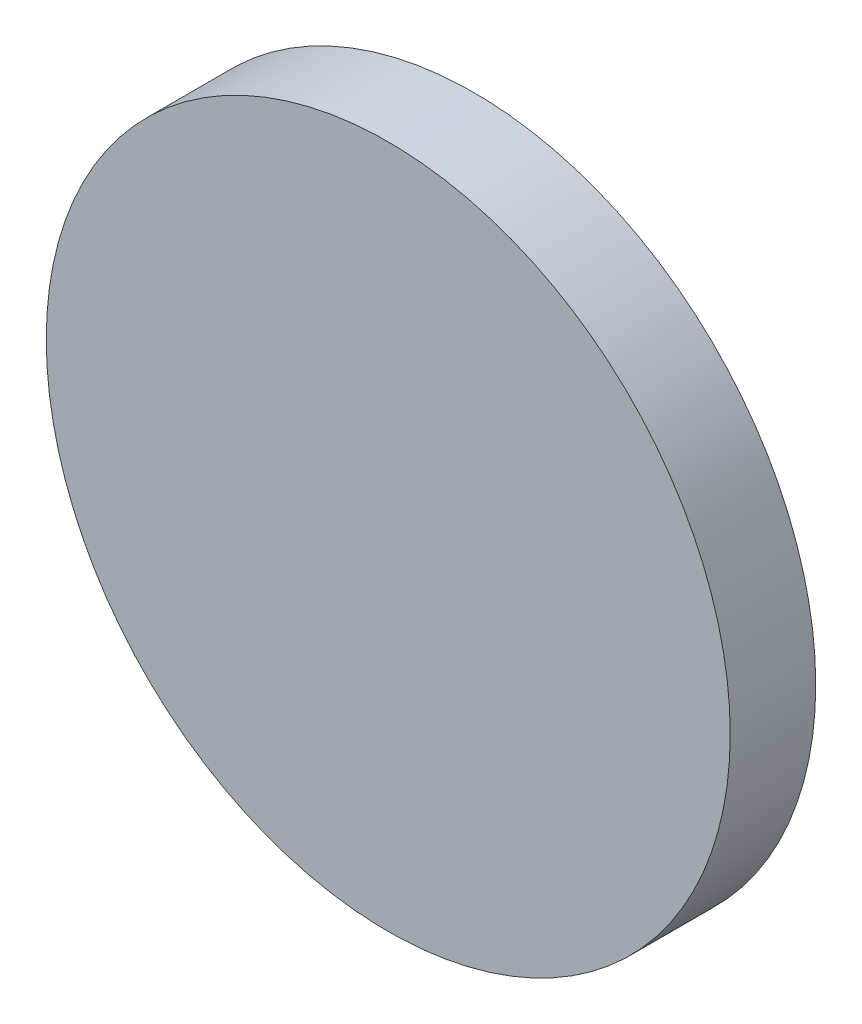
SolidWorks part; units mm, degrees
ref_plane "Front Plane" through (0, 0, 0) normal (0, 0, 1) x (1, 0, 0)
ref_plane "Top Plane" through (0, 0, 0) normal (0, 1, 0) x (1, 0, 0)
ref_plane "Right Plane" through (0, 0, 0) normal (1, 0, 0) x (0, 0, -1)
sketch "Sketch1" plane through (0, 0, 0) normal (0, 0, 1) x (1, 0, 0)
  circle A0 centre (-31.456, 78.0108) radius 8
extrude "Boss-Extrude1" add sketch "Sketch1" along normal blind 2
